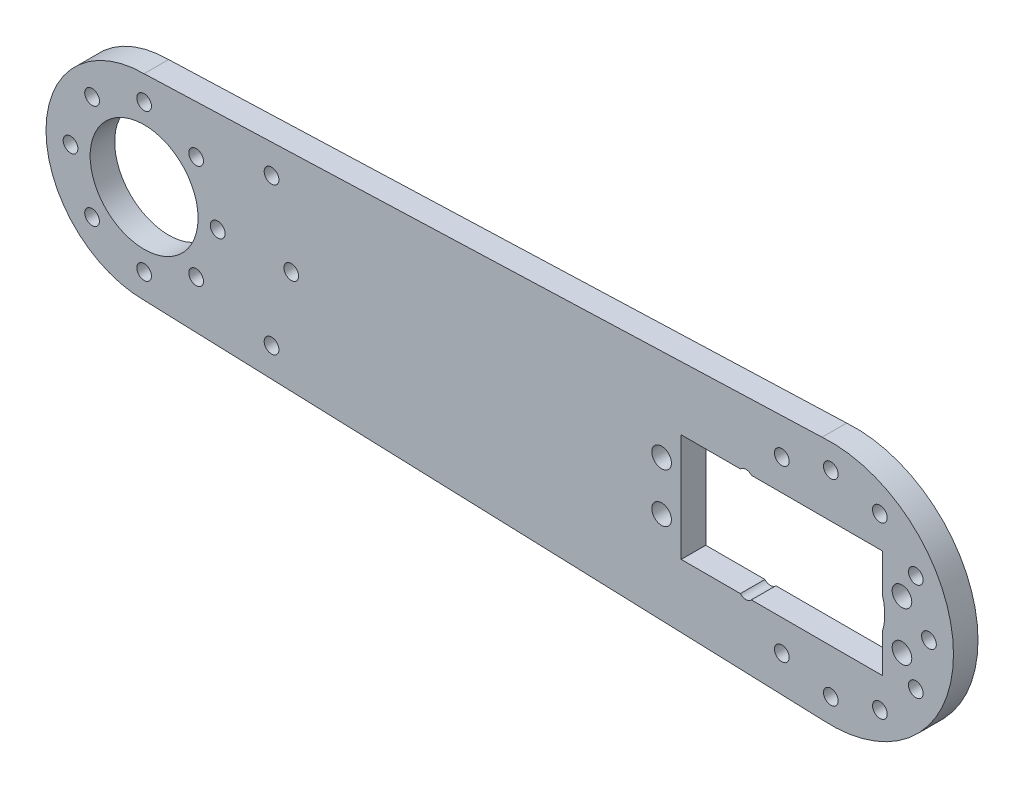
SolidWorks part; units mm, degrees
ref_plane "前视基准面" through (0, 0, 0) normal (0, 0, 1) x (1, 0, 0)
ref_plane "上视基准面" through (0, 0, 0) normal (0, 1, 0) x (1, 0, 0)
ref_plane "右视基准面" through (0, 0, 0) normal (1, 0, 0) x (0, 0, -1)
other "Configuration Table"
sketch "草图1" plane through (0, 0, 0) normal (0, 0, 1) x (1, 0, 0)
  line L0 (0, 0) -> (140, 0)
  line L1 (0, 35) -> (140, 25)
  line L2 (0, -35) -> (140, -25)
  circle A0 centre (0, 0) radius 35
  circle A1 centre (140, 0) radius 25
  dimension "D1" = 70
  dimension "D3" = 50
  dimension "D2" = 140
extrude "凸台-拉伸3" add sketch "草图1" along normal blind 5
sketch "草图4" plane through (0, 0, 5) normal (0, 0, 1) x (1, 0, 0)
  line L1 (-5, -5) -> (5, -5)
  line L2 (-5, -5) -> (-5, 5)
  line L3 (-5, 5) -> (5, 5)
  line L4 (5, -5) -> (5, 5)
  line L5 (-5, -5) -> (5, 5) construction
  line L6 (-5, 5) -> (5, -5) construction
  line L7 (135, -5) -> (145, -5)
  line L8 (135, -5) -> (135, 5)
  line L9 (135, 5) -> (145, 5)
  line L10 (145, -5) -> (145, 5)
  line L11 (135, -5) -> (145, 5) construction
  line L12 (135, 5) -> (145, -5) construction
  circle A0 centre (0, 0) radius 4
  circle A1 centre (-5, 5) radius 1.5
  circle A2 centre (5, 5) radius 1.5
  circle A3 centre (5, -5) radius 1.5
  circle A4 centre (-5, -5) radius 1.5
  circle A5 centre (140, 0) radius 4
  circle A6 centre (135, 5) radius 1.5
  circle A7 centre (145, 5) radius 1.5
  circle A8 centre (145, -5) radius 1.5
  circle A9 centre (135, -5) radius 1.5
  dimension "D1" = 8
  dimension "D4" = 3
  dimension "D6" = 8
  dimension "D9" = 3
  dimension "D2" = 10
  dimension "D3" = 10
  dimension "D7" = 10
  dimension "D8" = 10
  dimension "D5" = 4
  dimension "D10" = 4
extrude "切除-拉伸3" cut sketch "草图4" against normal blind 5 contours A5 | A0 | L2 A4 L1 | L1 A4 L2 | A6 | A9 | A8 | A7 | A1 | A2 | A3
sketch "草图5" plane through (0, 0, 5) normal (0, 0, 1) x (1, 0, 0)
  circle A0 centre (0, 0) radius 11
  circle A1 centre (140, 0) radius 11
  dimension "D1" = 22
  dimension "D2" = 22
extrude "切除-拉伸4" cut sketch "草图5" against normal blind 2
sketch "草图6" plane through (0, 0, 5) normal (0, 0, 1) x (1, 0, 0)
  circle A0 centre (0, 0) radius 30
  circle A1 centre (0, 30) radius 1.5
  circle A2 centre (15, 25.9808) radius 1.5
  circle A3 centre (25.9808, 15) radius 1.5
  circle A4 centre (30, 0) radius 1.5
  circle A5 centre (25.9808, -15) radius 1.5
  circle A6 centre (15, -25.9808) radius 1.5
  circle A7 centre (0, -30) radius 1.5
  circle A8 centre (-15, -25.9808) radius 1.5
  circle A9 centre (-25.9808, -15) radius 1.5
  circle A10 centre (-30, 0) radius 1.5
  circle A11 centre (-25.9808, 15) radius 1.5
  circle A12 centre (-15, 25.9808) radius 1.5
  circle A13 centre (140, 0) radius 20
  circle A14 centre (140, 20) radius 1.5
  circle A15 centre (150, 17.3205) radius 1.5
  circle A16 centre (157.3205, 10) radius 1.5
  circle A17 centre (160, 0) radius 1.5
  circle A18 centre (157.3205, -10) radius 1.5
  circle A19 centre (150, -17.3205) radius 1.5
  circle A20 centre (140, -20) radius 1.5
  circle A21 centre (130, -17.3205) radius 1.5
  circle A22 centre (122.6795, -10) radius 1.5
  circle A23 centre (120, 0) radius 1.5
  circle A24 centre (122.6795, 10) radius 1.5
  circle A25 centre (130, 17.3205) radius 1.5
  point P29 (0, 0)
  dimension "D1" = 60
  dimension "D2" = 3
  dimension "D4" = 40
  dimension "D5" = 3
  dimension "D3" = 12
  dimension "D6" = 12
extrude "切除-拉伸6" cut sketch "草图6" against normal through all contours A0 A12 | A11 | A1 | A2 | A3 | A4 | A5 | A6 | A7 | A8 | A9 | A10 | A25 | A14 | A15 | A16 | A17 | A18 | A19 | A20 | A21 | A22 | A23 | A24
sketch "草图7" plane through (0, 0, 5) normal (0, 0, 1) x (1, 0, 0)
  line L0 (140, 25) -> (0, 20)
  line L1 (140, -25) -> (0, -20)
  circle A0 centre (0, 0) radius 20
  circle A1 centre (140, 0) radius 25
  circle M1 centre (15, -25.9808) radius 1.5
  circle M2 centre (0, -30) radius 1.5
  circle M3 centre (-15, -25.9808) radius 1.5
  circle M4 centre (-25.9808, -15) radius 1.5
  circle M5 centre (-30, 0) radius 1.5
  circle M20 centre (15, 25.9808) radius 1.5
  circle M21 centre (-15, 25.9808) radius 1.5
  circle M22 centre (-25.9808, 15) radius 1.5
  circle M23 centre (0, 30) radius 1.5
  line M27 (0, -35) -> (140, -25)
  line M29 (140, 25) -> (0, 35)
  arc M30 (0, 35) -> (0, -35) centre (0, 0) ccw
  dimension "D1" = 40
extrude "切除-拉伸7" cut sketch "草图7" against normal blind 10 contours A1 L1 A0 L0 M29 M30 M27 M1 M3 M5 M21 M23 M22 M20 M4 M2
sketch "草图8" plane through (0, 0, 5) normal (0, 0, 1) x (1, 0, 0)
  circle A1 centre (0, 0) radius 11
extrude "切除-拉伸8" cut sketch "草图8" against normal blind 10
sketch "草图9" plane through (0, 0, 5) normal (0, 0, 1) x (1, 0, 0)
  circle A0 centre (0, 0) radius 15
  circle A1 centre (0, 15) radius 1.5
  circle A2 centre (10.6066, 10.6066) radius 1.5
  circle A3 centre (15, 0) radius 1.5
  circle A4 centre (10.6066, -10.6066) radius 1.5
  circle A5 centre (0, -15) radius 1.5
  circle A6 centre (-10.6066, -10.6066) radius 1.5
  circle A7 centre (-15, 0) radius 1.5
  circle A8 centre (-10.6066, 10.6066) radius 1.5
  dimension "D1" = 30
  dimension "D2" = 3
  dimension "D3" = 8
extrude "切除-拉伸9" cut sketch "草图9" against normal blind 10 contours A0 A4 | A2 | A3 | A5 | A6 | A7 | A8 | A1
sketch "草图10" plane through (0, 0, 3) normal (0, 0, 1) x (1, 0, 0)
  circle A0 centre (140, 0) radius 5
  dimension "D1" = 10
extrude "切除-拉伸10" cut sketch "草图10" against normal blind 10
sketch "草图11" plane through (0, 0, 5) normal (0, 0, 1) x (1, 0, 0)
  line L0 (140, 0) -> (110, 0)
  line L1 (140, 0) -> (130, 0)
  line L2 (110, 0) -> (105.5, 0)
  line L3 (150, -10) -> (110, -10)
  line L4 (150, -10) -> (150, 10)
  line L5 (150, 10) -> (110, 10)
  line L6 (110, -10) -> (110, 10)
  line L7 (150, -10) -> (110, 10) construction
  line L8 (150, 10) -> (110, -10) construction
  line L9 (105.5, 0) -> (105.5, 5)
  line L10 (130, -1000) -> (130, 49000) construction
  circle A0 centre (105.5, 5) radius 2
  circle A1 centre (105.5, -5) radius 2
  circle A2 centre (154.5, -5) radius 2
  circle A3 centre (154.5, 5) radius 2
  dimension "D6" = 4
  dimension "D1" = 30
  dimension "D2" = 10
  dimension "D3" = 20
  dimension "D4" = 4.5
  dimension "D5" = 5
extrude "切除-拉伸11" cut sketch "草图11" against normal blind 10
sketch "草图12" plane through (0, 0, 5) normal (0, 0, 1) x (1, 0, 0)
  line L0 (110, 10) -> (44831.3595, -22350.6798) construction
  line L1 (150, 10) -> (-44571.3595, -22350.6798) construction
  line L3 (109.5, -11) -> (150.5, -11)
  line L4 (109.5, -11) -> (109.5, 11)
  line L5 (109.5, 11) -> (150.5, 11)
  line L6 (150.5, -11) -> (150.5, 11)
  line L7 (109.5, -11) -> (150.5, 11) construction
  line L8 (109.5, 11) -> (150.5, -11) construction
  point P8 (130, 0)
  dimension "D1" = 41
  dimension "D2" = 22
extrude "切除-拉伸12" cut sketch "草图12" against normal blind 10
